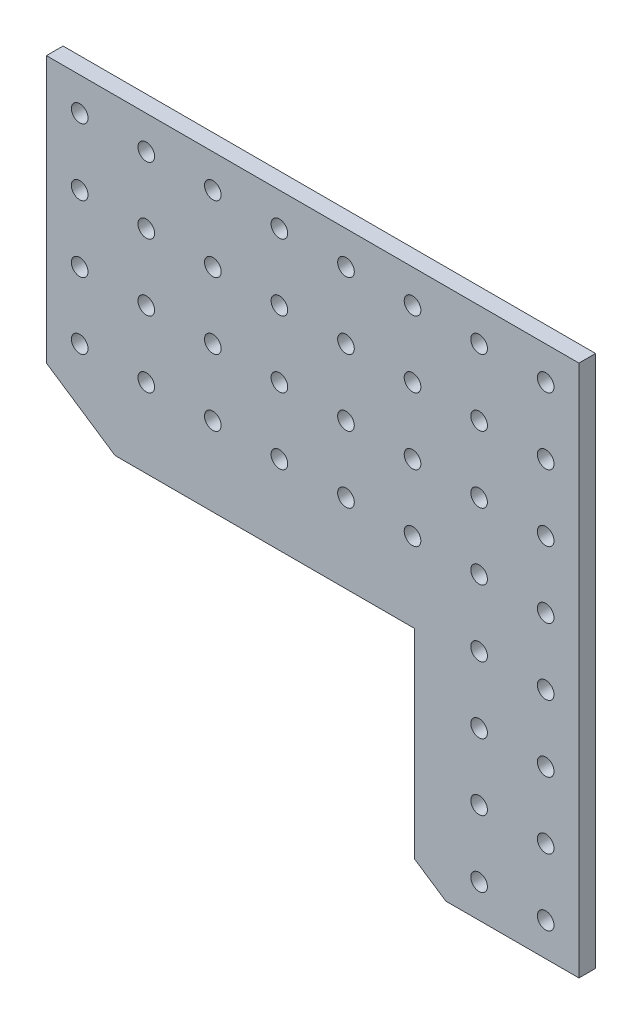
SolidWorks part; units mm, degrees
ref_plane "Front Plane" through (0, 0, 0) normal (0, 0, 1) x (1, 0, 0)
ref_plane "Top Plane" through (0, 0, 0) normal (0, 1, 0) x (1, 0, 0)
ref_plane "Right Plane" through (0, 0, 0) normal (1, 0, 0) x (0, 0, -1)
ref_plane "Plane1"
sketch "Sketch1" plane through (0, 0, 0) normal (0, 0, 1) x (1, 0, 0)
  line L0 (-136.0714, 83.0036) -> (16.3286, -18.5964)
  line L1 (16.3286, -18.5964) -> (67.1286, -18.5964)
  line L2 (67.1286, -18.5964) -> (67.1286, 184.6036)
  line L3 (67.1286, 184.6036) -> (-136.0714, 184.6036)
  line L4 (-136.0714, 184.6036) -> (-136.0714, 83.0036)
  dimension "D1" = 101.6
  dimension "D2" = 50.8
  dimension "D3" = 203.2
  dimension "D4" = 203.2
extrude "Extrusion1" add sketch "Sketch1" along normal blind 6.35
hole_wizard "Hole1" positions "Sketch3" profile "Sketch2" legacy end condition through all
sketch "Sketch3" plane through (0, 0, 6.35) normal (0, 0, 1) x (1, 0, 0)
  point P1 (-123.3714, 171.9036)
  point P2 (-97.9714, 171.9036)
  point P3 (-72.5714, 171.9036)
  point P4 (-47.1714, 171.9036)
  point P5 (-21.7714, 171.9036)
  point P6 (3.6286, 171.9036)
  point P7 (29.0286, 171.9036)
  point P8 (54.4286, 171.9036)
  point P9 (-123.3714, 146.5036)
  point P10 (-97.9714, 146.5036)
  point P11 (-72.5714, 146.5036)
  point P12 (-47.1714, 146.5036)
  point P13 (-21.7714, 146.5036)
  point P14 (3.6286, 146.5036)
  point P15 (29.0286, 146.5036)
  point P16 (54.4286, 146.5036)
  point P17 (-123.3714, 121.1036)
  point P18 (-97.9714, 121.1036)
  point P19 (-72.5714, 121.1036)
  point P20 (-47.1714, 121.1036)
  point P21 (-21.7714, 121.1036)
  point P22 (3.6286, 121.1036)
  point P23 (29.0286, 121.1036)
  point P24 (54.4286, 121.1036)
  point P25 (-123.3714, 95.7036)
  point P26 (-97.9714, 95.7036)
  point P27 (-72.5714, 95.7036)
  point P28 (-47.1714, 95.7036)
  point P29 (-21.7714, 95.7036)
  point P30 (3.6286, 95.7036)
  point P31 (29.0286, 95.7036)
  point P32 (54.4286, 95.7036)
  point P33 (54.4286, 70.3036)
  point P34 (54.4286, 44.9036)
  point P35 (54.4286, 19.5036)
  point P36 (54.4286, -5.8964)
  point P37 (29.0286, 70.3036)
  point P38 (29.0286, 44.9036)
  point P39 (29.0286, 19.5036)
  point P40 (29.0286, -5.8964)
sketch "Sketch2" plane through (-123.3714, 171.9036, 6.35) normal (1, 0, 0) x (0, -1, 0)
  line L0 (0, 0) -> (0, 6.35)
  line L1 (0, 6.35) -> (3.175, 6.35)
  line L2 (3.175, 6.35) -> (3.175, 0)
  line L3 (3.175, 0) -> (0, 0)
  line L4 (0, 110) -> (0, -10) construction
  dimension "Diameter" = 6.35
  dimension "Depth" = 6.35
sketch "Sketch4" plane through (0, 0, 0) normal (0, 0, -1) x (-1, 0, 0)
  line L0 (33.684, 65.5453) -> (33.684, 14.7453)
  line L1 (33.684, 14.7453) -> (109.884, 65.5453)
  line L2 (109.884, 65.5453) -> (33.684, 65.5453)
  dimension "D1" = 50.8
  dimension "D2" = 76.2
extrude "Extrusion2" cut sketch "Sketch4" against normal blind 25.4
sketch "Sketch5" plane through (0, 0, 6.35) normal (0, 0, 1) x (1, 0, 0)
  line L0 (16.3286, -18.5964) -> (67.1286, -18.5964) construction
  line L1 (-33.684, 65.5453) -> (4.416, 65.5453)
  line L2 (-33.684, 65.5453) -> (-33.684, -18.5964)
  line L3 (-33.684, -18.5964) -> (4.416, -18.5964)
  line L4 (4.416, 65.5453) -> (4.416, -18.5964)
  dimension "D1" = 38.1
extrude "Cut-Extrude1" cut sketch "Sketch5" against normal through all
